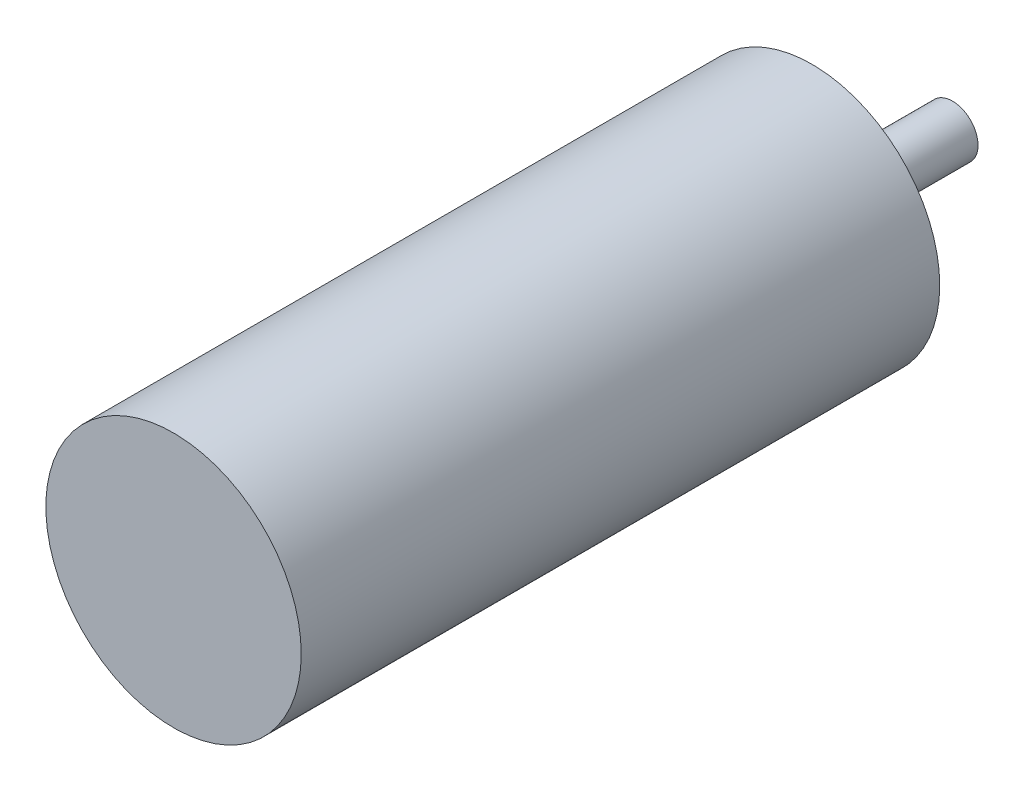
SolidWorks part; units mm, degrees
material "Zinc AC43A (Zn-4Al-2.5Cu-0.04Mg; Number 2 Die Casting Alloy; Zamak 2), Die Cast"
ref_plane "Front Plane" through (0, 0, 0) normal (0, 0, 1) x (1, 0, 0)
ref_plane "Top Plane" through (0, 0, 0) normal (0, 1, 0) x (1, 0, 0)
ref_plane "Right Plane" through (0, 0, 0) normal (1, 0, 0) x (0, 0, -1)
sketch "Sketch1" plane through (0, 0, 0) normal (0, 0, 1) x (1, 0, 0)
  circle A0 centre (0, 0) radius 25
extrude "Boss-Extrude1" add sketch "Sketch1" along normal blind 125
sketch "Sketch2" plane through (0, 0, 0) normal (0, 0, -1) x (-1, 0, 0)
  circle A0 centre (0, 0) radius 12.5
extrude "Boss-Extrude2" add sketch "Sketch2" along normal blind 2.5
sketch "Sketch3" plane through (0, 0, -2.5) normal (0, 0, -1) x (-1, 0, 0)
  circle A0 centre (0, 0) radius 5
  dimension "D1" = 10
extrude "Boss-Extrude3" add sketch "Sketch3" along normal blind 25
